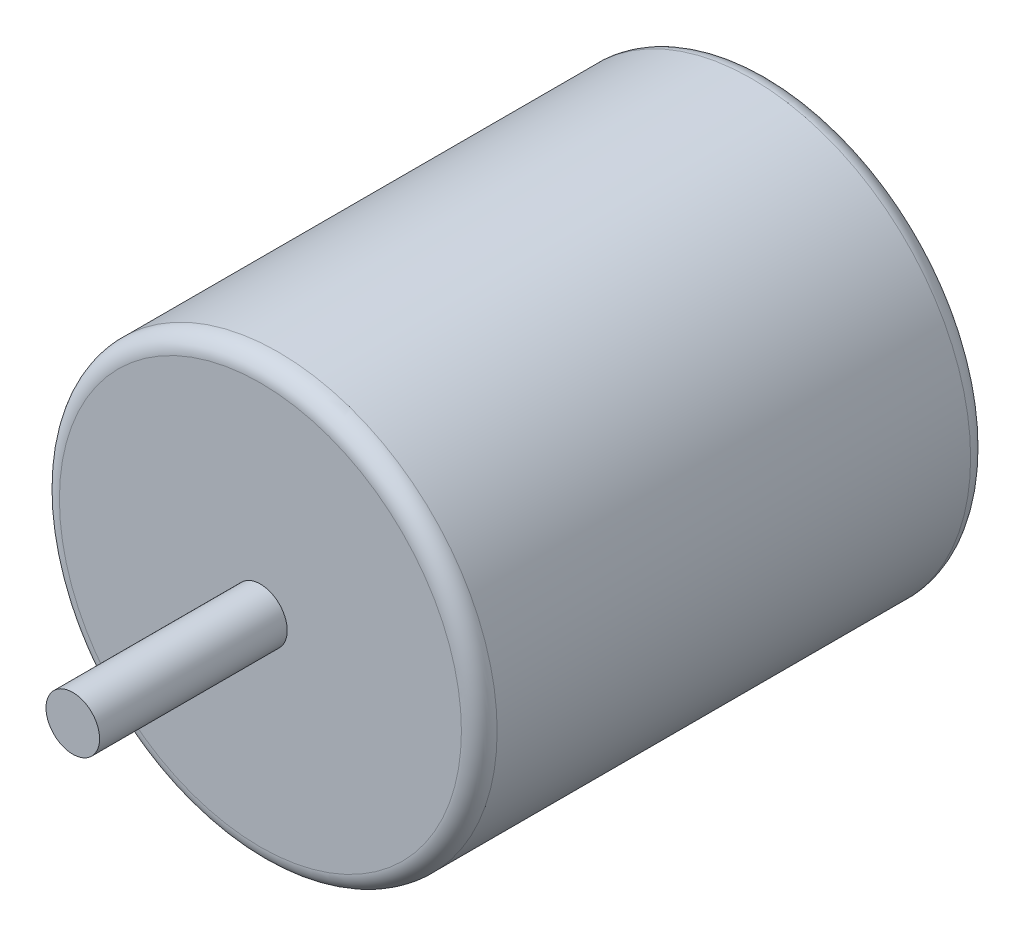
SolidWorks part; units mm, degrees
ref_plane "Front Plane" through (0, 0, 0) normal (0, 0, 1) x (1, 0, 0)
ref_plane "Top Plane" through (0, 0, 0) normal (0, 1, 0) x (1, 0, 0)
ref_plane "Right Plane" through (0, 0, 0) normal (1, 0, 0) x (0, 0, -1)
sketch "Sketch1" plane through (0, 0, 0) normal (0, 0, 1) x (1, 0, 0)
  circle A0 centre (0, 0) radius 24.5
  dimension "D1" = 49
extrude "Boss-Extrude1" add sketch "Sketch1" along normal blind 57
sketch "Sketch2" plane through (0, 0, 57) normal (0, 0, 1) x (1, 0, 0)
  circle A0 centre (0, 0) radius 3
  dimension "D1" = 6
extrude "Boss-Extrude2" add sketch "Sketch2" along normal blind 21
fillet "Fillet1" radius 2 2 edges at (24.5, 0, 57) (24.5, 0, 0)
